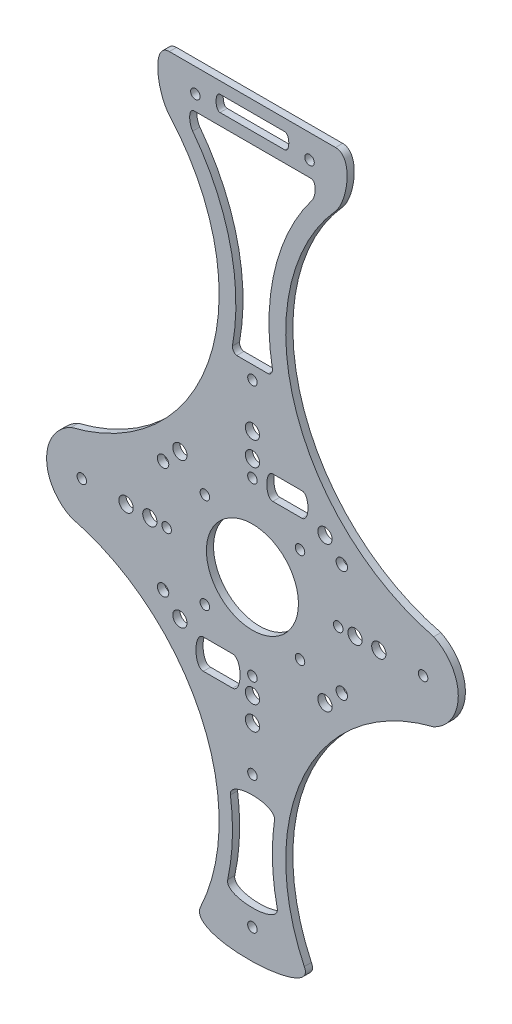
SolidWorks part; units mm, degrees
ref_plane "前视基准面" through (0, 0, 0) normal (0, 0, 1) x (1, 0, 0)
ref_plane "上视基准面" through (0, 0, 0) normal (0, 1, 0) x (1, 0, 0)
ref_plane "右视基准面" through (0, 0, 0) normal (1, 0, 0) x (0, 0, -1)
sketch "Model" plane through (0, 0, 0) normal (0, 0, 1) x (1, 0, 0)
  line L0 (164.2499, 187.0888) -> (146.7872, 187.0888)
  line L1 (159.067, 178.8832) -> (146.7872, 178.8832)
  line L2 (150.0887, 138.8371) -> (146.7872, 138.8371)
  line L3 (143.4857, 138.8371) -> (146.7872, 138.8371)
  line L4 (134.5074, 178.8832) -> (146.7872, 178.8832)
  line L5 (151.0532, 121.0703) -> (157.2092, 121.0703)
  line L6 (151.0532, 116.067) -> (157.2092, 116.067)
  line L7 (136.47, 84.0904) -> (142.626, 84.0904)
  line L8 (136.47, 77.8479) -> (142.626, 77.8479)
  line L9 (139.9743, 181.3177) -> (153.6002, 181.3177)
  line L10 (139.9743, 184.6313) -> (153.6002, 184.6313)
  line L11 (129.3246, 187.0888) -> (146.7872, 187.0888)
  circle A0 centre (156.7872, 110.1398) radius 1
  circle A1 centre (136.7872, 110.1398) radius 1
  circle A2 centre (136.7872, 90.1398) radius 1
  circle A3 centre (156.7872, 90.1398) radius 1
  circle A4 centre (168.354, 100.1398) radius 1.5
  circle A5 centre (146.7872, 121.7066) radius 1.5
  circle A6 centre (125.2205, 100.1398) radius 1.5
  circle A7 centre (146.7872, 78.5731) radius 1.5
  circle A8 centre (146.7872, 126.7066) radius 1.5
  circle A9 centre (120.2205, 100.1398) radius 1.5
  circle A10 centre (146.7872, 73.5731) radius 1.5
  circle A11 centre (173.354, 100.1398) radius 1.5
  circle A12 centre (146.7872, 118.171) radius 1
  circle A13 centre (128.756, 100.1398) radius 1
  circle A14 centre (146.7872, 82.1086) radius 1
  circle A15 centre (164.8184, 100.1398) radius 1
  circle A16 centre (162.0372, 115.3898) radius 1.5
  circle A17 centre (131.5372, 115.3898) radius 1.5
  circle A18 centre (131.5372, 84.8898) radius 1.5
  circle A19 centre (162.0372, 84.8898) radius 1.5
  circle A20 centre (182.6572, 100.1398) radius 1
  circle A21 centre (146.7872, 136.0369) radius 1
  circle A22 centre (110.9172, 100.1398) radius 1
  circle A23 centre (146.7872, 64.2428) radius 1
  arc A24 (184.891, 91.9296) -> (184.891, 108.3501) centre (180.9546, 100.1398) ccw
  arc A25 (108.6834, 108.3501) -> (108.6834, 91.9296) centre (112.6199, 100.1398) ccw
  circle A26 centre (146.7872, 36.4198) radius 1
  arc A27 (165.7942, 119.1469) -> (184.891, 108.3501) centre (194.7856, 148.1382) ccw
  arc A28 (164.2499, 175.4982) -> (165.7942, 119.1469) centre (194.7856, 148.1382) ccw
  arc A29 (108.6834, 108.3501) -> (127.7802, 119.1469) centre (98.7888, 148.1382) ccw
  arc A30 (127.7802, 81.1328) -> (108.6834, 91.9296) centre (98.7888, 52.1414) ccw
  arc A31 (165.7942, 81.1328) -> (157.6831, 34.6943) centre (194.7856, 52.1414) ccw
  arc A32 (184.891, 91.9296) -> (165.7942, 81.1328) centre (194.7856, 52.1414) ccw
  arc A33 (135.8914, 34.6943) -> (127.7802, 81.1328) centre (98.7888, 52.1414) ccw
  circle A34 centre (158.7872, 182.0998) radius 1
  circle A35 centre (134.7872, 182.0998) radius 1
  arc A36 (142.5873, 140.124) -> (134.2278, 175.0542) centre (98.8103, 148.1127) ccw
  arc A37 (151.4142, 58.1799) -> (151.9869, 42.4846) centre (195.473, 51.9294) ccw
  arc A38 (159.3466, 175.0542) -> (150.9871, 140.124) centre (194.7642, 148.1127) ccw
  arc A39 (141.5876, 42.4846) -> (142.1602, 58.1799) centre (98.1014, 51.9294) ccw
  circle A40 centre (128.0017, 111.8543) radius 1.2
  circle A41 centre (165.5728, 111.8543) radius 1.2
  circle A42 centre (128.0017, 88.4254) radius 1.2
  circle A43 centre (165.5728, 88.4254) radius 1.2
  circle A44 centre (146.7872, 100.1398) radius 9.6721
  arc A45 (127.7802, 119.1469) -> (129.3246, 175.4982) centre (98.7888, 148.1382) ccw
  spline S0 degree 3 poles (0, 0) (0.3333, 0) (0.6667, 0) (1, 0) knots 0 0 0 0 1 1 1 1
  spline S1 degree 3 poles (0, 0) (0.3333, 0) (0.6667, 0) (1, 0) knots 0 0 0 0 1 1 1 1
  spline S2 degree 3 poles (135.8914, 34.6943) (132.8003, 28.1209) (160.7742, 29.1209) (157.6831, 34.6943) knots 0 0 0 0 21.791721 21.791721 21.791721 21.791721
  spline S3 degree 3 poles (150.9871, 140.124) (151.081, 139.6093) (150.6119, 138.8371) (150.0887, 138.8371) knots 0 0 0 0 1.569452 1.569452 1.569452 1.569452
  spline S4 degree 3 poles (142.5873, 140.124) (142.4934, 139.6093) (142.9626, 138.8371) (143.4857, 138.8371) knots 0 0 0 0 1.569452 1.569452 1.569452 1.569452
  spline S5 degree 3 poles (159.067, 178.8832) (160.3467, 178.8832) (160.1214, 176.0727) (159.3466, 175.0542) knots 0 0 0 0 3.839142 3.839142 3.839142 3.839142
  spline S6 degree 3 poles (134.5074, 178.8832) (133.2277, 178.8832) (133.4531, 176.0727) (134.2278, 175.0542) knots 0 0 0 0 3.839142 3.839142 3.839142 3.839142
  spline S7 degree 3 poles (142.1602, 58.1799) (141.727, 61.2339) (151.8475, 61.2339) (151.4142, 58.1799) knots 0 0 0 0 9.253948 9.253948 9.253948 9.253948
  spline S8 degree 3 poles (141.5876, 42.4846) (140.8518, 39.0971) (152.7226, 39.0971) (151.9869, 42.4846) knots 0 0 0 0 10.399316 10.399316 10.399316 10.399316
  spline S9 degree 3 poles (136.47, 84.0904) (134.3892, 84.0904) (134.3892, 77.8479) (136.47, 77.8479) knots 0 0 0 0 6.242464 6.242464 6.242464 6.242464
  spline S10 degree 3 poles (142.626, 84.0904) (144.7068, 84.0904) (144.7068, 77.8479) (142.626, 77.8479) knots 0 0 0 0 6.242464 6.242464 6.242464 6.242464
  spline S11 degree 3 poles (0, 0) (0.3333, 0) (0.6667, 0) (1, 0) knots 0 0 0 0 1 1 1 1
  spline S12 degree 3 poles (157.2092, 121.0703) (158.877, 121.0703) (158.877, 116.067) (157.2092, 116.067) knots 0 0 0 0 5.0033 5.0033 5.0033 5.0033
  spline S13 degree 3 poles (151.0532, 121.0703) (149.3854, 121.0703) (149.3854, 116.067) (151.0532, 116.067) knots 0 0 0 0 5.0033 5.0033 5.0033 5.0033
  spline S14 degree 3 poles (139.9743, 184.6313) (138.8698, 184.6313) (138.8698, 181.3177) (139.9743, 181.3177) knots 0 0 0 0 3.313543 3.313543 3.313543 3.313543
  spline S15 degree 3 poles (153.6002, 184.6313) (154.7047, 184.6313) (154.7047, 181.3177) (153.6002, 181.3177) knots 0 0 0 0 3.313543 3.313543 3.313543 3.313543
  spline S16 degree 3 poles (164.2499, 187.0888) (168.1134, 187.0888) (166.8281, 178.3756) (164.2499, 175.4982) knots 0 0 0 0 11.590604 11.590604 11.590604 11.590604
  spline S17 degree 3 poles (129.3246, 187.0888) (125.461, 187.0888) (126.7464, 178.3756) (129.3246, 175.4982) knots 0 0 0 0 11.590604 11.590604 11.590604 11.590604
extrude "凸台-拉伸1" add sketch "Model" along normal blind 1.5 contours A37 S8 A39 S7 | L1 L4 S6 A36 S4 L3 L2 S3 A38 S5 | L9 S15 L10 S14 | L7 S10 L8 S9 | L5 S12 L6 S13 | L0 L11 S17 A45 A29 A25 A30 A33 S2 A31 A32 A24 A27 A28 S16 | A7 | A6 | A5 | A4 | A3 | A2 | A1 | A0 | A15 | A14 | A13 | A12 | A11 | A10 | A9 | A8 | A23 | A22 | A21 | A20 | A19 | A18 | A17 | A16 | A26 | A43 | A42 | A41 | A40 | A35 | A34 | A44 | S0 S1 S11
